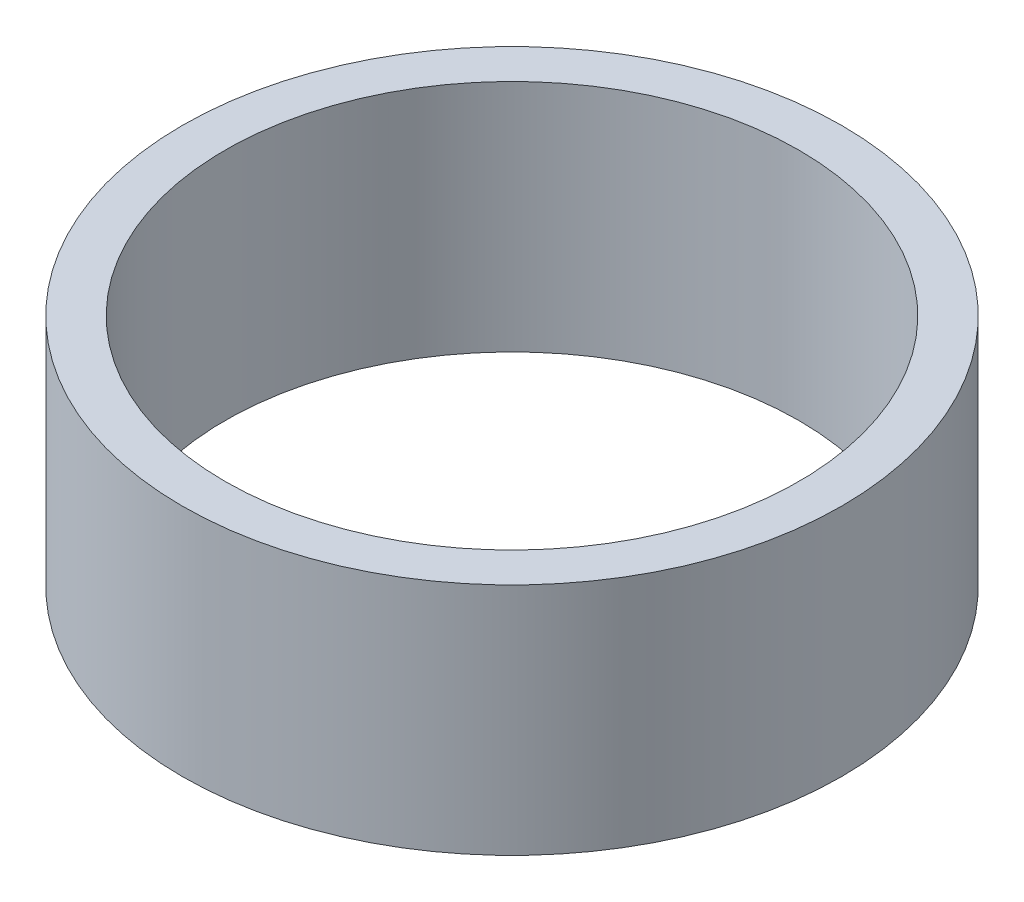
SolidWorks part; units mm, degrees
material "Corrugated Paper"
ref_plane "Front Plane" through (0, 0, 0) normal (0, 0, 1) x (1, 0, 0)
ref_plane "Top Plane" through (0, 0, 0) normal (0, 1, 0) x (1, 0, 0)
ref_plane "Right Plane" through (0, 0, 0) normal (1, 0, 0) x (0, 0, -1)
sketch "Sketch1" plane through (0, 0, 0) normal (0, 0, 1) x (1, 0, 0)
  line L0 (0, 0) -> (0, 74.3474) construction
  line L1 (62.23, 0) -> (71.501, 0)
  line L2 (62.23, 0) -> (62.23, 50.8)
  line L3 (71.501, 0) -> (71.501, 50.8)
  line L4 (62.23, 50.8) -> (71.501, 50.8)
  dimension "D1" = 124.46
  dimension "D2" = 143.002
  dimension "D3" = 50.8
revolve "Revolve1" add sketch "Sketch1" angle 360 about L0
